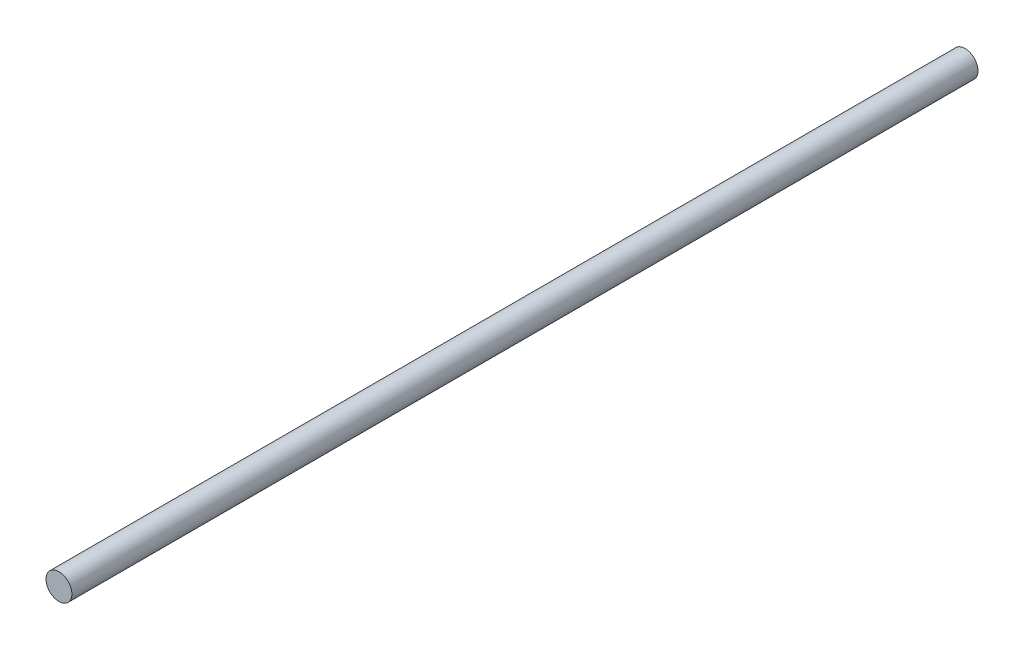
SolidWorks part; units mm, degrees
ref_plane "Front Plane" through (0, 0, 0) normal (0, 0, 1) x (1, 0, 0)
ref_plane "Top Plane" through (0, 0, 0) normal (0, 1, 0) x (1, 0, 0)
ref_plane "Right Plane" through (0, 0, 0) normal (1, 0, 0) x (0, 0, -1)
sketch "Sketch1" plane through (0, 0, 0) normal (0, 0, 1) x (1, 0, 0)
  circle A0 centre (0, 0) radius 10
  dimension "D1" = 20
extrude "Boss-Extrude1" add sketch "Sketch1" along normal blind 700
